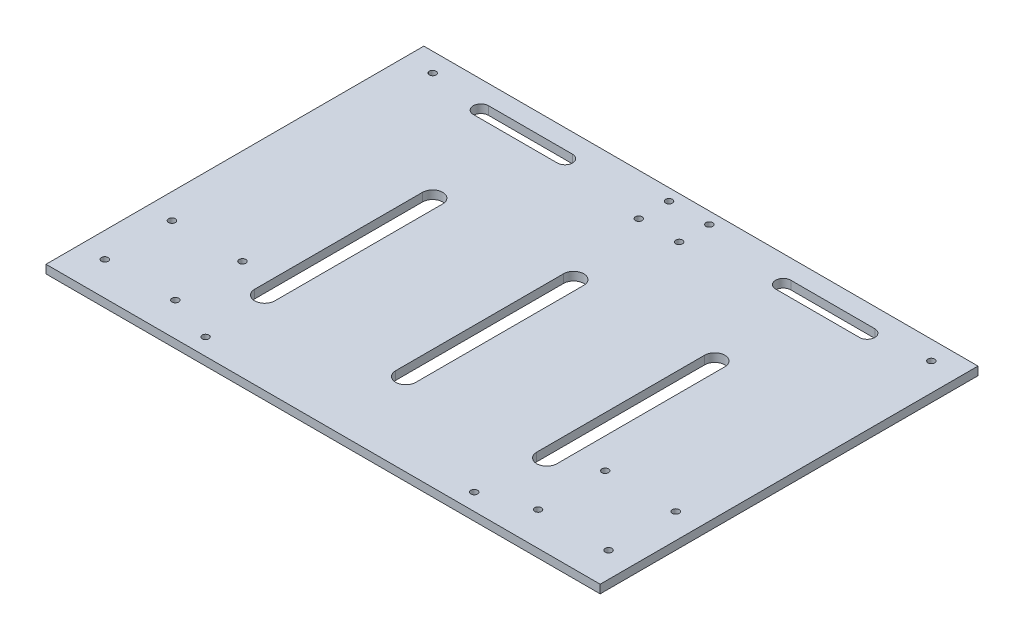
SolidWorks part; units mm, degrees
ref_plane "前视基准面" through (0, 0, 0) normal (0, 0, 1) x (1, 0, 0)
ref_plane "上视基准面" through (0, 0, 0) normal (0, 1, 0) x (1, 0, 0)
ref_plane "右视基准面" through (0, 0, 0) normal (1, 0, 0) x (0, 0, -1)
sketch "草图1" plane through (0, 0, 0) normal (0, 1, 0) x (1, 0, 0)
  line L1 (-15.2985, 237.1784) -> (314.7015, 237.1784)
  line L2 (-15.2985, 237.1784) -> (-15.2985, 12.1784)
  line L3 (-15.2985, 12.1784) -> (314.7015, 12.1784)
  line L4 (314.7015, 237.1784) -> (314.7015, 12.1784)
  dimension "D1" = 330
  dimension "D2" = 225
extrude "凸台-拉伸1" add sketch "草图1" along normal blind 5
sketch "草图2" plane through (0, 5, 0) normal (0, 1, 0) x (1, 0, 0)
  line L0 (149.7015, 237.1784) -> (149.7015, 12.1784) construction
  line L1 (314.7015, 237.1784) -> (-15.2985, 237.1784) construction
  line L2 (-15.2985, 12.1784) -> (314.7015, 12.1784) construction
  line L3 (137.7015, 230.1784) -> (137.7015, 206.5288) construction
  line L4 (137.7015, 230.1784) -> (161.7015, 212.1784) construction
  line L5 (161.7015, 230.1784) -> (137.7015, 212.1784) construction
  line L6 (149.7015, 221.1784) -> (50149.7015, 221.1784) construction
  line L7 (34.7015, 221.1784) -> (84.7015, 221.1784) construction
  line L8 (34.7015, 225.7154) -> (84.7015, 225.7154)
  line L9 (34.7015, 216.6414) -> (84.7015, 216.6414)
  line L10 (264.7015, 221.1784) -> (214.7015, 221.1784) construction
  line L11 (264.7015, 225.7154) -> (214.7015, 225.7154)
  line L12 (264.7015, 216.6414) -> (214.7015, 216.6414)
  circle A0 centre (137.7015, 230.1784) radius 2
  circle A1 centre (161.7015, 230.1784) radius 2
  circle A2 centre (137.7015, 212.1784) radius 2
  circle A3 centre (161.7015, 212.1784) radius 2
  arc A4 (34.7015, 225.7154) -> (34.7015, 216.6414) centre (34.7015, 221.1784) ccw
  arc A5 (84.7015, 216.6414) -> (84.7015, 225.7154) centre (84.7015, 221.1784) ccw
  arc A6 (264.7015, 225.7154) -> (264.7015, 216.6414) centre (264.7015, 221.1784) cw
  arc A7 (214.7015, 216.6414) -> (214.7015, 225.7154) centre (214.7015, 221.1784) cw
  point P14 (149.7015, 221.1784)
  point P20 (59.7015, 221.1784)
  point P27 (239.7015, 221.1784)
  dimension "D1" = 4
  dimension "D9" = 4
  dimension "D10" = 4
  dimension "D2" = 24
  dimension "D3" = 18
  dimension "D4" = 18
  dimension "D5" = 24
  dimension "D6" = 7
  dimension "D7" = 50
  dimension "D8" = 90
extrude "切除-拉伸1" cut sketch "草图2" against normal through all
sketch "草图3" plane through (0, 5, 0) normal (0, 1, 0) x (1, 0, 0)
  line L0 (-14.3127, 52.1784) -> (315.6873, 52.1784) construction
  line L1 (-15.2985, 237.1784) -> (-15.2985, 12.1784) construction
  line L2 (-15.2985, 12.1784) -> (314.7015, 12.1784) construction
  line L3 (314.7015, 12.1784) -> (314.7015, 237.1784) construction
  line L4 (149.7015, 462.1784) -> (149.7015, 12.1784) construction
  circle A0 centre (-0.2985, 32.1784) radius 2
  circle A1 centre (-0.2985, 72.1784) radius 2
  circle A2 centre (41.7015, 32.1784) radius 2
  circle A3 centre (41.7015, 72.1784) radius 2
  circle A4 centre (257.7015, 72.1784) radius 2
  circle A5 centre (257.7015, 32.1784) radius 2
  circle A6 centre (299.7015, 72.1784) radius 2
  circle A7 centre (299.7015, 32.1784) radius 2
  point P15 (149.7015, 237.1784)
  dimension "D5" = 4
  dimension "D6" = 4
  dimension "D1" = 40
  dimension "D2" = 42
  dimension "D3" = 20
  dimension "D4" = 15
extrude "切除-拉伸2" cut sketch "草图3" against normal through all
sketch "草图5" plane through (0, 5, 0) normal (0, 1, 0) x (1, 0, 0)
  line L0 (149.7015, 237.1784) -> (149.7015, -49762.8216) construction
  line L1 (314.7015, 237.1784) -> (-15.2985, 237.1784) construction
  line L2 (-28.7911, 85.1784) -> (354.7976, 85.1784) construction
  line L3 (149.7015, 161.4116) -> (149.7015, 61.4116) construction
  line L4 (155.7015, 161.4116) -> (155.7015, 61.4116)
  line L5 (143.7015, 161.4116) -> (143.7015, 61.4116)
  line L6 (233.7015, 161.4116) -> (233.7015, 61.4116) construction
  line L7 (239.7015, 161.4116) -> (239.7015, 61.4116)
  line L8 (227.7015, 161.4116) -> (227.7015, 61.4116)
  line L9 (65.7015, 161.4116) -> (65.7015, 61.4116) construction
  line L10 (59.7015, 161.4116) -> (59.7015, 61.4116)
  line L11 (71.7015, 161.4116) -> (71.7015, 61.4116)
  arc A0 (155.7015, 161.4116) -> (143.7015, 161.4116) centre (149.7015, 161.4116) ccw
  arc A1 (143.7015, 61.4116) -> (155.7015, 61.4116) centre (149.7015, 61.4116) ccw
  arc A2 (239.7015, 161.4116) -> (227.7015, 161.4116) centre (233.7015, 161.4116) ccw
  arc A3 (227.7015, 61.4116) -> (239.7015, 61.4116) centre (233.7015, 61.4116) ccw
  arc A4 (59.7015, 161.4116) -> (71.7015, 161.4116) centre (65.7015, 161.4116) cw
  arc A5 (71.7015, 61.4116) -> (59.7015, 61.4116) centre (65.7015, 61.4116) cw
  point P4 (149.7015, 237.1784)
  point P9 (149.7015, 111.4116)
  point P17 (233.7015, 111.4116)
  point P23 (65.7015, 111.4116)
  dimension "D3" = 6
  dimension "D1" = 152
  dimension "D2" = 100
  dimension "D5" = 84
  dimension "D4" = 2
extrude "切除-拉伸4" cut sketch "草图5" against normal through all
sketch "草图6" plane through (0, 5, 0) normal (0, 1, 0) x (1, 0, 0)
  line L0 (314.7015, 12.1784) -> (-15.2985, 237.1784) construction
  line L1 (314.7015, 237.1784) -> (-15.2985, 12.1784) construction
  line L2 (149.7015, 237.1784) -> (149.7015, 50237.1784) construction
  line L3 (314.7015, 237.1784) -> (-15.2985, 237.1784) construction
  line L4 (149.7015, 22.1784) -> (-49850.2985, 22.1784) construction
  line L5 (-15.2985, 12.1784) -> (314.7015, 12.1784) construction
  circle A0 centre (1.226, 225.9117) radius 2
  circle A1 centre (298.1769, 225.9117) radius 2
  circle A2 centre (69.7015, 22.1784) radius 2
  circle A3 centre (229.7015, 22.1784) radius 2
  point P14 (149.7015, 237.1784)
  dimension "D1" = 4
  dimension "D4" = 4
  dimension "D2" = 20
  dimension "D3" = 10
  dimension "D5" = 80
extrude "切除-拉伸5" cut sketch "草图6" against normal through all
